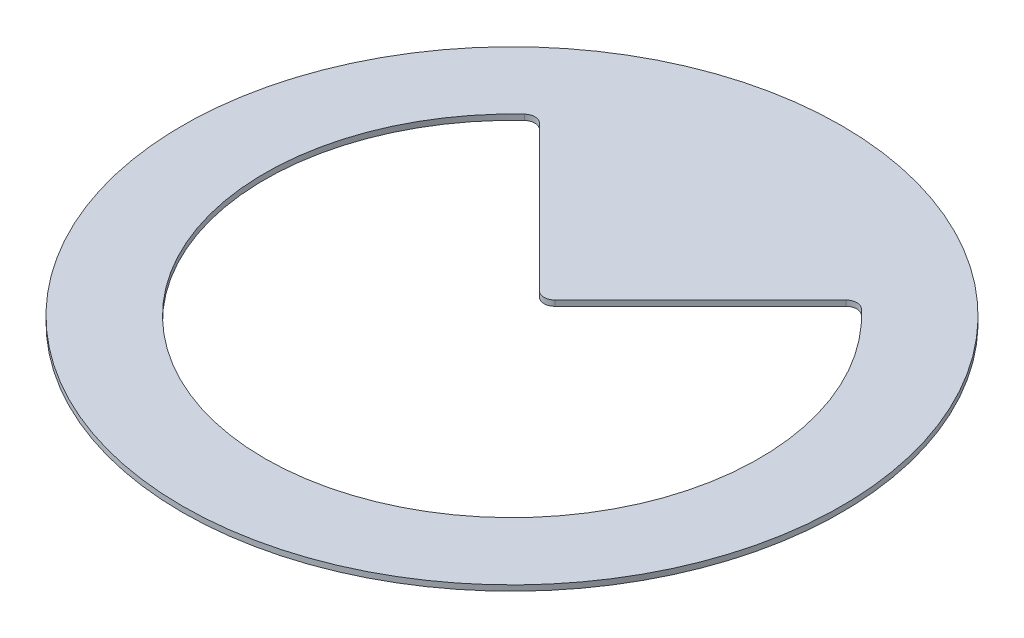
SolidWorks part; units mm, degrees
ref_plane "Front" through (0, 0, 0) normal (0, 0, 1) x (1, 0, 0)
ref_plane "Top" through (0, 0, 0) normal (0, 1, 0) x (1, 0, 0)
ref_plane "Right" through (0, 0, 0) normal (1, 0, 0) x (0, 0, -1)
sketch "Sketch1" plane through (0, 0, 0) normal (0, 1, 0) x (1, 0, 0)
  line L1 (0, 55.799) -> (0, -45) construction
  line L3 (-29.2214, 34.2214) -> (0, 5)
  line L4 (0, 5) -> (29.2214, 34.2214)
  line L5 (0, -50) -> (0, -56.3751) construction
  arc A2 (-29.2214, 34.2214) -> (29.2214, 34.2214) centre (0, 0) ccw
  circle A3 centre (0, 0) radius 60
  dimension "D1" = 120
  dimension "D3" = 90
  dimension "D4" = 90
  dimension "D5" = 5
extrude "Boss-Extrude1" add sketch "Sketch1" along normal blind 1
fillet "Fillet1" radius 2 3 edges at (-29.2214, 0.5, -34.2214) (29.2214, 0.5, -34.2214) (0, 0.5, -5)
